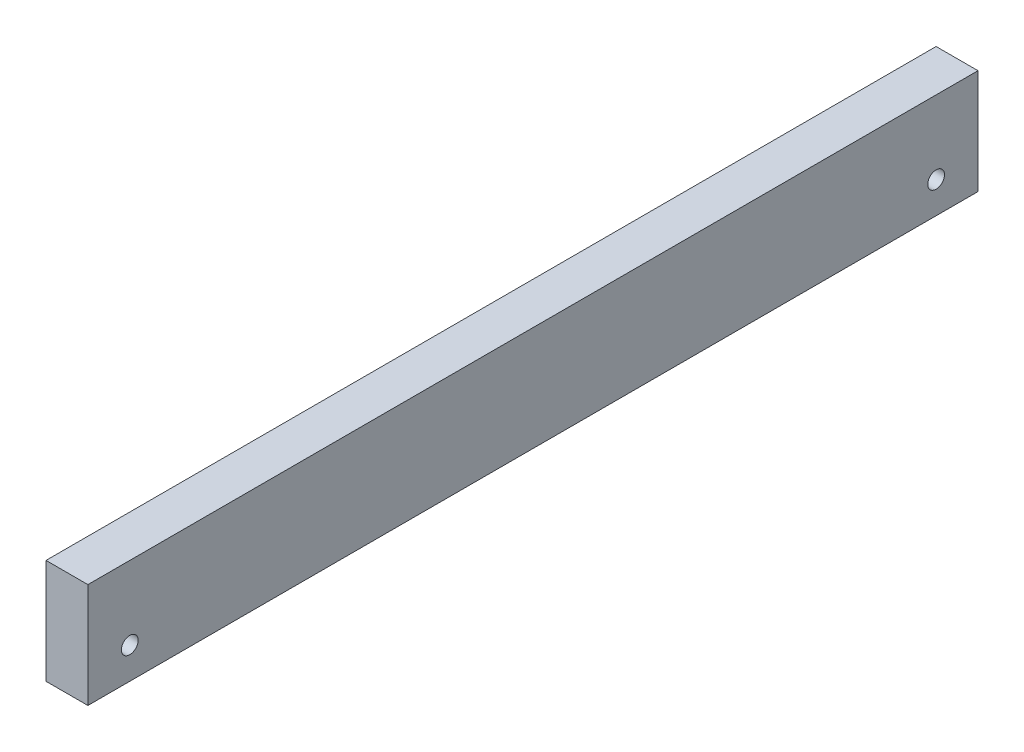
SolidWorks part; units mm, degrees
ref_plane "Front Plane" through (0, 0, 0) normal (0, 0, 1) x (1, 0, 0)
ref_plane "Top Plane" through (0, 0, 0) normal (0, 1, 0) x (1, 0, 0)
ref_plane "Right Plane" through (0, 0, 0) normal (1, 0, 0) x (0, 0, -1)
sketch "Sketch1" plane through (0, 0, 0) normal (0, 0, 1) x (1, 0, 0)
  line L1 (0, 0) -> (20, 0)
  line L2 (0, 0) -> (0, 50)
  line L3 (0, 50) -> (20, 50)
  line L4 (20, 0) -> (20, 50)
  dimension "D1" = 20
  dimension "D2" = 50
extrude "Extrude1" add sketch "Sketch1" along normal blind 425
hole_wizard "Ø8.0 (8) Diameter Hole1" positions "3DSketch1" profile "Sketch2" hole size "Ø8.0" standard "Ansi Metric" end condition through all
sketch3d "3DSketch1"
  line L0 (20, 0, 425) -> (20, 0, 0) construction
  line L1 (20, 0, 0) -> (20, 50, 0) construction
  line L2 (20, 0, 425) -> (20, 50, 425) construction
  point P0 (20, 15, 405)
  point P2 (20, 15, 20)
  dimension "D1" = 15
  dimension "D2" = 15
  dimension "D3" = 20
  dimension "D4" = 20
sketch "Sketch2" plane through (20, 15, 405) normal (0, 1, 0) x (0, 0, -1)
  line L0 (0, 0) -> (0, 20)
  line L1 (0, 20) -> (4, 20)
  line L2 (4, 20) -> (4, 0)
  line L5 (4, 0) -> (0, 0)
  line L11 (0, -6.35) -> (0, 107.95) construction
  dimension "Thru Hole Dia." = 8
  dimension "Thru Hole Depth" = 20
